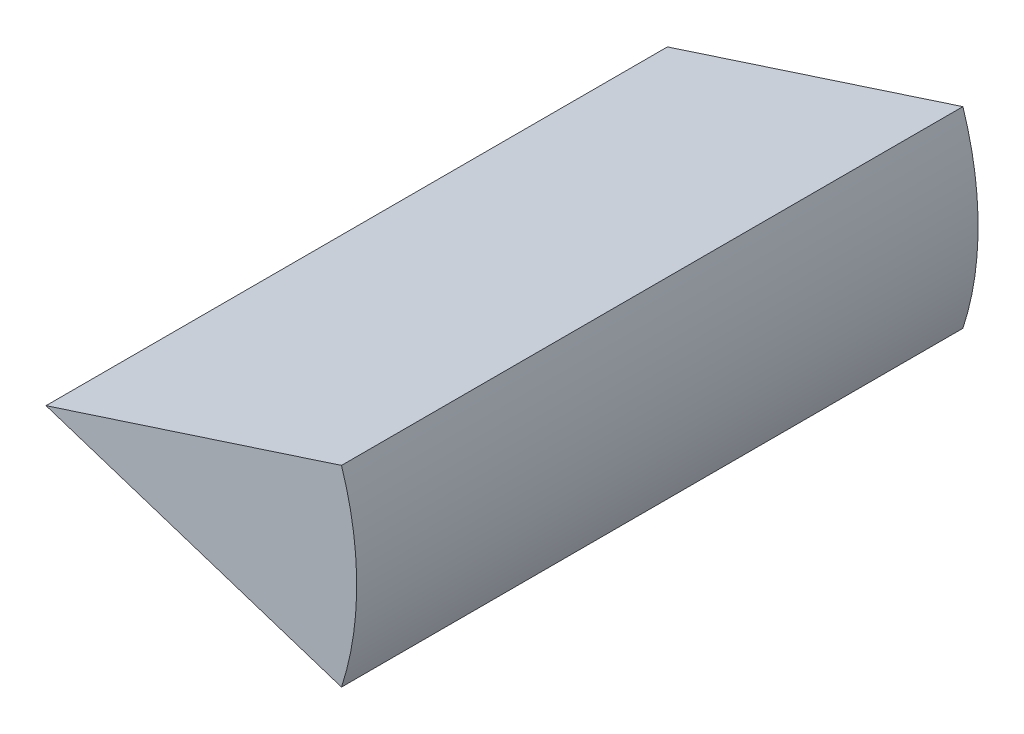
SolidWorks part; units mm, degrees
ref_plane "Alzado" through (0, 0, 0) normal (0, 0, 1) x (1, 0, 0)
ref_plane "Planta" through (0, 0, 0) normal (0, 1, 0) x (1, 0, 0)
ref_plane "Vista lateral" through (0, 0, 0) normal (1, 0, 0) x (0, 0, -1)
sketch "Croquis1" plane through (0, 0, 0) normal (0, 0, 1) x (1, 0, 0)
  line L2 (0, 0) -> (23.7764, 7.7254)
  line L3 (0, 0) -> (23.7764, -7.7254)
  arc A0 (23.7764, -7.7254) -> (23.7764, 7.7254) centre (0, 0) ccw
  dimension "D1" = 50
  dimension "D2" = 36
extrude "Saliente-Extruir1" add sketch "Croquis1" along normal blind 50
sketch "Croquis2" plane through (0, 0, 0) normal (0, 0, -1) x (-1, 0, 0)
  circle A0 centre (-19.1139, 0.4556) radius 4.9657
extrude "Cortar-Extruir1" cut sketch "Croquis2" against normal blind 10
